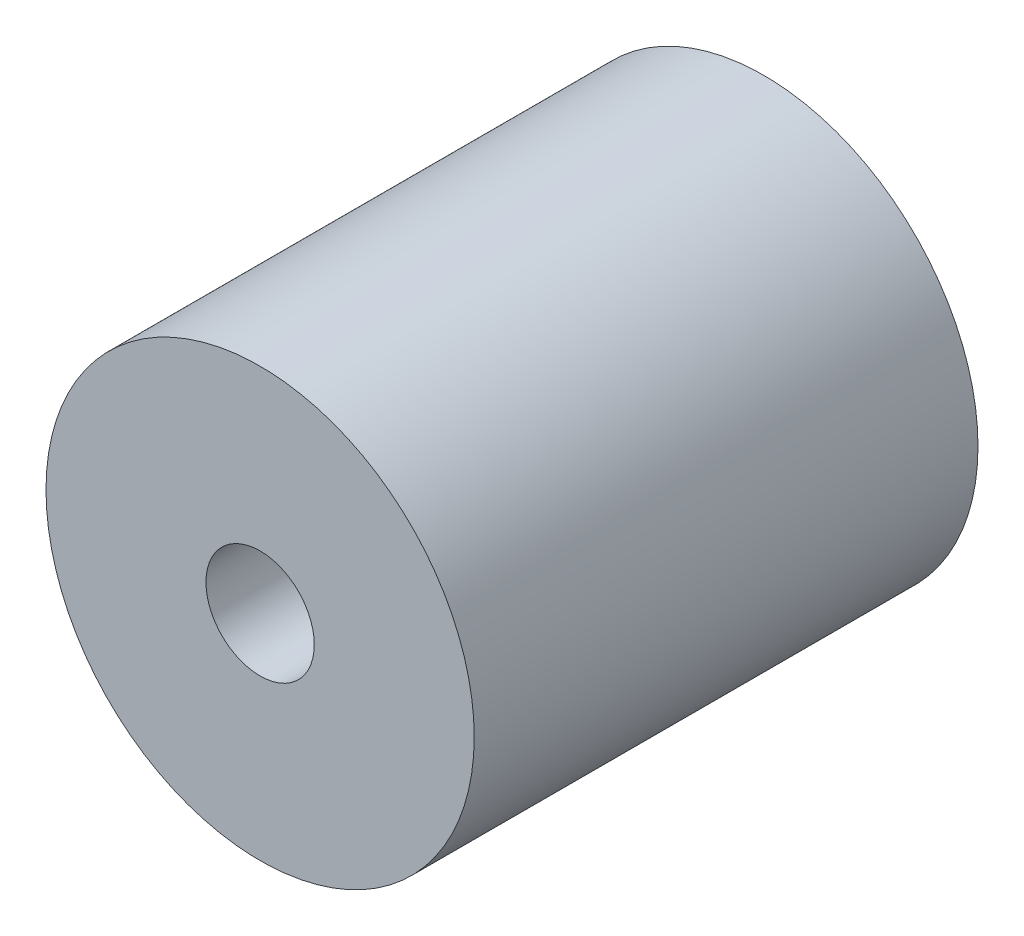
SolidWorks part; units mm, degrees
ref_plane "Płaszczyzna przednia" through (0, 0, 0) normal (0, 0, 1) x (1, 0, 0)
ref_plane "Płaszczyzna górna" through (0, 0, 0) normal (0, 1, 0) x (1, 0, 0)
ref_plane "Płaszczyzna prawa" through (0, 0, 0) normal (1, 0, 0) x (0, 0, -1)
sketch "Szkic1" plane through (0, 0, 0) normal (0, 0, 1) x (1, 0, 0)
  circle A0 centre (0, 0) radius 4.25
  dimension "D1" = 8.5
extrude "Dodanie-wyciągnięcie1" add sketch "Szkic1" along normal blind 10
sketch "Szkic3" plane through (0, 0, 0) normal (0, 0, -1) x (-1, 0, 0)
  circle A0 centre (0, 0) radius 1.075
  dimension "D1" = 2.15
extrude "Wytnij-wyciągnięcie1" cut sketch "Szkic3" against normal up to next
